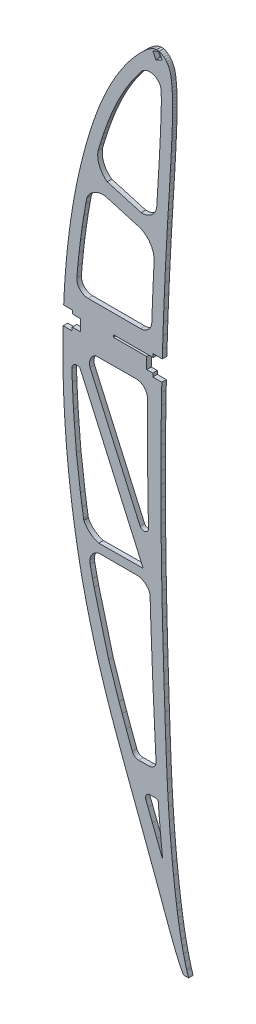
SolidWorks part; units mm, degrees
ref_plane "前视基准面" through (0, 0, 0) normal (0, 0, 1) x (1, 0, 0)
ref_plane "上视基准面" through (0, 0, 0) normal (0, 1, 0) x (1, 0, 0)
ref_plane "右视基准面" through (0, 0, 0) normal (1, 0, 0) x (0, 0, -1)
sketch "Model" plane through (0, 0, 0) normal (0, 0, 1) x (1, 0, 0)
  line L0 (913.8384, 184.2905) -> (912.3155, 187.0491)
  line L1 (912.3155, 187.0491) -> (911.2172, 189.5713)
  line L2 (911.2172, 189.5713) -> (910.1429, 192.0532)
  line L3 (910.1429, 192.0532) -> (909.1681, 194.525)
  line L4 (909.1681, 194.525) -> (908.2131, 197.0037)
  line L5 (908.2131, 197.0037) -> (907.2748, 199.4892)
  line L6 (907.2748, 199.4892) -> (906.3493, 201.9792)
  line L7 (906.3493, 201.9792) -> (905.4326, 204.4726)
  line L8 (905.4326, 204.4726) -> (904.519, 206.9671)
  line L9 (904.519, 206.9671) -> (903.6062, 209.4636)
  line L10 (903.6062, 209.4636) -> (901.77, 214.4493)
  line L11 (901.77, 214.4493) -> (899.921, 219.4284)
  line L12 (899.921, 219.4284) -> (898.0633, 224.4031)
  line L13 (898.0633, 224.4031) -> (896.1967, 229.3734)
  line L14 (896.1967, 229.3734) -> (894.3261, 234.3435)
  line L15 (894.3261, 234.3435) -> (892.4535, 239.3136)
  line L16 (892.4535, 239.3136) -> (890.5819, 244.2857)
  line L17 (890.5819, 244.2857) -> (888.7243, 249.2343)
  line L18 (888.7243, 249.2343) -> (886.8804, 254.1876)
  line L19 (886.8804, 254.1876) -> (885.0604, 259.147)
  line L20 (885.0604, 259.147) -> (883.2718, 264.1187)
  line L21 (883.2718, 264.1187) -> (881.5267, 269.1043)
  line L22 (881.5267, 269.1043) -> (879.8328, 274.1092)
  line L23 (879.8328, 274.1092) -> (878.2, 279.1357)
  line L24 (878.2, 279.1357) -> (876.669, 284.0757)
  line L25 (876.669, 284.0757) -> (875.2083, 289.0357)
  line L26 (875.2083, 289.0357) -> (873.8177, 294.0158)
  line L27 (873.8177, 294.0158) -> (872.4994, 299.015)
  line L28 (872.4994, 299.015) -> (871.2533, 304.0334)
  line L29 (871.2533, 304.0334) -> (870.0806, 309.0691)
  line L30 (870.0806, 309.0691) -> (868.983, 314.124)
  line L31 (868.983, 314.124) -> (867.9765, 319.1108)
  line L32 (867.9765, 319.1108) -> (867.0426, 324.1099)
  line L33 (867.0426, 324.1099) -> (866.1792, 329.121)
  line L34 (866.1792, 329.121) -> (865.3824, 334.143)
  line L35 (865.3824, 334.143) -> (864.6511, 339.1759)
  line L36 (864.6511, 339.1759) -> (863.9826, 344.2185)
  line L37 (863.9826, 344.2185) -> (863.3756, 349.2699)
  line L38 (863.3756, 349.2699) -> (862.8318, 354.2969)
  line L39 (862.8318, 354.2969) -> (862.3469, 359.3286)
  line L40 (862.3469, 359.3286) -> (861.9218, 364.3648)
  line L41 (861.9218, 364.3648) -> (861.5576, 369.4047)
  line L42 (861.5576, 369.4047) -> (861.2534, 374.4483)
  line L43 (861.2534, 374.4483) -> (861.0119, 379.4975)
  line L44 (861.0119, 379.4975) -> (860.8323, 384.5495)
  line L45 (860.8323, 384.5495) -> (860.7144, 389.6112)
  line L46 (860.7144, 389.6112) -> (860.6627, 394.6717)
  line L47 (860.6627, 394.6717) -> (860.6749, 399.7331)
  line L48 (860.6749, 399.7331) -> (860.7676, 405.5689)
  line L49 (904.2453, 405.7391) -> (904.1791, 401.7577)
  line L50 (904.1791, 401.7577) -> (904.0837, 396.6977)
  line L51 (904.0837, 396.6977) -> (904.0034, 391.6364)
  line L52 (904.0034, 391.6364) -> (903.9412, 386.5729)
  line L53 (903.9412, 386.5729) -> (903.8937, 381.516)
  line L54 (903.8937, 381.516) -> (903.8633, 376.4599)
  line L55 (903.8633, 376.4599) -> (903.8468, 371.4043)
  line L56 (903.8468, 371.4043) -> (903.8462, 366.3495)
  line L57 (903.8462, 366.3495) -> (903.8587, 361.2952)
  line L58 (903.8587, 361.2952) -> (903.8853, 356.2386)
  line L59 (903.8853, 356.2386) -> (903.9239, 351.1814)
  line L60 (903.9239, 351.1814) -> (903.9755, 346.1269)
  line L61 (903.9755, 346.1269) -> (904.0389, 341.0748)
  line L62 (904.0389, 341.0748) -> (904.1143, 336.0233)
  line L63 (904.1143, 336.0233) -> (904.2007, 330.9723)
  line L64 (904.2007, 330.9723) -> (904.2991, 325.9218)
  line L65 (904.2991, 325.9218) -> (904.4086, 320.8697)
  line L66 (904.4086, 320.8697) -> (904.5291, 315.8172)
  line L67 (904.5291, 315.8172) -> (904.6595, 310.7661)
  line L68 (904.6595, 310.7661) -> (904.8009, 305.7164)
  line L69 (904.8009, 305.7164) -> (904.9492, 300.6691)
  line L70 (904.9492, 300.6691) -> (905.1056, 295.6211)
  line L71 (905.1056, 295.6211) -> (905.2679, 290.5734)
  line L72 (905.2679, 290.5734) -> (905.4353, 285.5239)
  line L73 (905.4353, 285.5239) -> (905.6068, 280.4736)
  line L74 (905.6068, 280.4736) -> (905.7822, 275.4234)
  line L75 (905.7822, 275.4234) -> (905.9666, 270.3746)
  line L76 (905.9666, 270.3746) -> (906.1639, 265.3284)
  line L77 (906.1639, 265.3284) -> (906.3812, 260.2831)
  line L78 (906.3812, 260.2831) -> (906.6225, 255.2388)
  line L79 (906.6225, 255.2388) -> (906.8957, 250.195)
  line L80 (906.8957, 250.195) -> (907.205, 245.1526)
  line L81 (907.205, 245.1526) -> (907.5555, 240.1051)
  line L82 (907.5555, 240.1051) -> (907.9518, 235.0626)
  line L83 (907.9518, 235.0626) -> (908.395, 230.0242)
  line L84 (908.395, 230.0242) -> (908.8881, 224.9899)
  line L85 (908.8881, 224.9899) -> (909.4359, 219.961)
  line L86 (909.4359, 219.961) -> (910.0397, 214.9355)
  line L87 (910.0397, 214.9355) -> (910.7024, 209.9147)
  line L88 (910.7024, 209.9147) -> (911.0609, 207.3889)
  line L89 (911.0609, 207.3889) -> (911.4403, 204.866)
  line L90 (911.4403, 204.866) -> (911.8445, 202.3483)
  line L91 (911.8445, 202.3483) -> (912.2804, 199.8379)
  line L92 (912.2804, 199.8379) -> (912.7521, 197.3341)
  line L93 (912.7521, 197.3341) -> (913.2653, 194.8401)
  line L94 (913.2653, 194.8401) -> (913.8243, 192.3551)
  line L95 (913.8243, 192.3551) -> (914.4448, 189.8348)
  line L96 (914.4448, 189.8348) -> (915.1109, 187.3255)
  line L97 (915.1109, 187.3255) -> (915.2832, 186.7532)
  line L98 (915.2832, 186.7532) -> (916.0384, 184.2905)
  line L99 (882.9494, 412.239) -> (882.9494, 413.239)
  line L100 (882.9494, 413.239) -> (900.4381, 413.239)
  line L101 (903.1073, 531.427) -> (900.3814, 530.1739)
  line L102 (900.3814, 530.1739) -> (901.6334, 527.4489)
  line L103 (901.6334, 527.4489) -> (904.3594, 528.701)
  line L104 (904.3594, 528.701) -> (903.1073, 531.427)
  line L105 (882.9494, 412.239) -> (897.6033, 412.239)
  line L106 (869.4735, 449.5555) -> (869.8575, 452.0169)
  line L107 (869.8575, 452.0169) -> (870.7414, 457.0572)
  line L108 (870.7414, 457.0572) -> (871.2274, 459.6062)
  line L109 (876.1273, 479.9715) -> (876.8839, 482.5223)
  line L110 (876.8839, 482.5223) -> (877.6738, 485.0581)
  line L111 (877.6738, 485.0581) -> (878.4997, 487.5767)
  line L112 (878.4997, 487.5767) -> (879.365, 490.0807)
  line L113 (879.365, 490.0807) -> (880.273, 492.5783)
  line L114 (880.273, 492.5783) -> (880.7549, 493.8511)
  line L115 (880.7549, 493.8511) -> (881.251, 495.1262)
  line L116 (881.251, 495.1262) -> (881.7583, 496.3907)
  line L117 (881.7583, 496.3907) -> (882.2786, 497.6475)
  line L118 (882.2786, 497.6475) -> (882.8123, 498.8974)
  line L119 (882.8123, 498.8974) -> (883.3579, 500.1358)
  line L120 (883.3579, 500.1358) -> (883.9169, 501.3614)
  line L121 (883.9169, 501.3614) -> (884.5204, 502.6386)
  line L122 (884.5204, 502.6386) -> (885.1408, 503.9045)
  line L123 (885.1408, 503.9045) -> (885.7787, 505.1609)
  line L124 (885.7787, 505.1609) -> (886.4355, 506.4076)
  line L125 (886.4355, 506.4076) -> (887.1119, 507.6471)
  line L126 (887.1119, 507.6471) -> (887.8072, 508.8774)
  line L127 (887.8072, 508.8774) -> (888.5236, 510.0993)
  line L128 (888.5236, 510.0993) -> (889.3233, 511.4151)
  line L129 (889.3233, 511.4151) -> (890.1441, 512.7152)
  line L130 (890.1441, 512.7152) -> (890.9834, 513.9946)
  line L131 (890.9834, 513.9946) -> (891.84, 515.247)
  line L132 (891.84, 515.247) -> (892.712, 516.4692)
  line L133 (892.712, 516.4692) -> (893.5962, 517.6556)
  line L134 (893.5962, 517.6556) -> (894.4959, 518.8083)
  line L135 (894.4959, 518.8083) -> (894.6454, 518.9923)
  line L136 (903.9715, 515.9403) -> (903.9975, 514.9313)
  line L137 (903.9975, 514.9313) -> (904.0137, 513.707)
  line L138 (904.0137, 513.707) -> (904.0158, 512.4744)
  line L139 (904.0158, 512.4744) -> (904.0052, 511.2385)
  line L140 (904.0052, 511.2385) -> (903.983, 509.9924)
  line L141 (903.983, 509.9924) -> (903.9527, 508.7401)
  line L142 (903.9527, 508.7401) -> (903.9144, 507.4816)
  line L143 (903.9144, 507.4816) -> (903.8709, 506.2139)
  line L144 (903.8709, 506.2139) -> (903.8242, 504.9389)
  line L145 (903.8242, 504.9389) -> (903.7755, 503.6601)
  line L146 (903.7755, 503.6601) -> (903.7249, 502.3826)
  line L147 (903.7249, 502.3826) -> (903.6722, 501.1048)
  line L148 (903.6722, 501.1048) -> (903.6176, 499.8269)
  line L149 (903.6176, 499.8269) -> (903.561, 498.5508)
  line L150 (903.561, 498.5508) -> (903.5013, 497.2708)
  line L151 (903.5013, 497.2708) -> (903.4409, 495.9972)
  line L152 (903.4409, 495.9972) -> (903.311, 493.4393)
  line L153 (903.311, 493.4393) -> (903.1719, 490.8805)
  line L154 (903.1719, 490.8805) -> (903.0267, 488.3194)
  line L155 (903.0267, 488.3194) -> (902.8753, 485.756)
  line L156 (902.8753, 485.756) -> (902.7205, 483.1856)
  line L157 (902.7205, 483.1856) -> (902.5638, 480.6174)
  line L158 (902.5638, 480.6174) -> (902.406, 478.0458)
  line L159 (902.406, 478.0458) -> (902.2499, 475.4687)
  line L160 (902.2499, 475.4687) -> (902.0949, 472.8935)
  line L161 (902.0949, 472.8935) -> (902.0028, 471.3652)
  line L162 (900.8224, 449.6864) -> (900.5768, 444.5302)
  line L163 (900.5768, 444.5302) -> (900.3472, 439.3722)
  line L164 (900.3472, 439.3722) -> (900.1327, 434.2139)
  line L165 (900.1327, 434.2139) -> (899.8292, 426.3183)
  line L166 (894.8329, 421.5104) -> (871.8067, 421.5104)
  line L167 (866.8255, 426.9432) -> (867.2416, 431.7331)
  line L168 (867.2416, 431.7331) -> (867.7661, 436.8274)
  line L169 (867.7661, 436.8274) -> (868.3743, 441.9069)
  line L170 (868.3743, 441.9069) -> (869.0702, 446.9705)
  line L171 (869.0702, 446.9705) -> (869.4735, 449.5555)
  line L172 (897.9183, 396.3811) -> (897.9024, 393.3658)
  line L173 (897.9024, 393.3658) -> (897.8924, 388.2083)
  line L174 (869.7615, 336.4945) -> (869.1231, 340.5859)
  line L175 (869.1231, 340.5859) -> (868.4003, 345.6376)
  line L176 (865.157, 379.1332) -> (865.0474, 381.0069)
  line L177 (865.0474, 381.0069) -> (864.8146, 386.0729)
  line L178 (864.8146, 386.0729) -> (864.6437, 391.1474)
  line L179 (875.1445, 401.3147) -> (892.8985, 401.4074)
  line L180 (880.2019, 470.228) -> (895.1891, 465.9129)
  line L181 (879.3627, 464.3047) -> (894.6921, 459.8753)
  line L182 (861.0134, 413.5675) -> (861.1482, 416.6981)
  line L183 (861.1482, 416.6981) -> (861.4416, 421.8318)
  line L184 (861.4416, 421.8318) -> (861.8135, 427.0219)
  line L185 (861.8135, 427.0219) -> (862.2638, 432.2055)
  line L186 (862.2638, 432.2055) -> (862.7966, 437.3807)
  line L187 (862.7966, 437.3807) -> (863.4149, 442.5446)
  line L188 (863.4149, 442.5446) -> (864.1229, 447.6964)
  line L189 (864.1229, 447.6964) -> (864.9246, 452.8342)
  line L190 (864.9246, 452.8342) -> (865.8229, 457.9573)
  line L191 (865.8229, 457.9573) -> (866.3206, 460.5675)
  line L192 (866.3206, 460.5675) -> (866.8445, 463.1718)
  line L193 (866.8445, 463.1718) -> (867.3956, 465.7703)
  line L194 (867.3956, 465.7703) -> (867.9731, 468.362)
  line L195 (867.9731, 468.362) -> (868.5789, 470.9479)
  line L196 (868.5789, 470.9479) -> (869.212, 473.5279)
  line L197 (869.212, 473.5279) -> (869.8744, 476.1013)
  line L198 (869.8744, 476.1013) -> (870.5831, 478.7357)
  line L199 (870.5831, 478.7357) -> (871.3243, 481.3615)
  line L200 (871.3243, 481.3615) -> (872.1, 483.9768)
  line L201 (872.1, 483.9768) -> (872.9112, 486.5807)
  line L202 (872.9112, 486.5807) -> (873.7609, 489.1722)
  line L203 (873.7609, 489.1722) -> (874.6523, 491.7516)
  line L204 (874.6523, 491.7516) -> (875.5852, 494.3177)
  line L205 (875.5852, 494.3177) -> (876.0869, 495.6429)
  line L206 (876.0869, 495.6429) -> (876.6008, 496.9635)
  line L207 (876.6008, 496.9635) -> (877.128, 498.2778)
  line L208 (877.128, 498.2778) -> (877.6694, 499.5856)
  line L209 (877.6694, 499.5856) -> (878.2252, 500.8871)
  line L210 (878.2252, 500.8871) -> (878.7953, 502.1812)
  line L211 (878.7953, 502.1812) -> (879.3817, 503.467)
  line L212 (879.3817, 503.467) -> (880.0149, 504.8069)
  line L213 (880.0149, 504.8069) -> (880.6665, 506.1366)
  line L214 (880.6665, 506.1366) -> (881.3375, 507.4581)
  line L215 (881.3375, 507.4581) -> (882.0289, 508.7705)
  line L216 (882.0289, 508.7705) -> (882.7407, 510.0748)
  line L217 (882.7407, 510.0748) -> (883.4738, 511.372)
  line L218 (883.4738, 511.372) -> (884.2303, 512.6623)
  line L219 (884.2303, 512.6623) -> (885.0726, 514.0483)
  line L220 (885.0726, 514.0483) -> (885.9395, 515.4214)
  line L221 (885.9395, 515.4214) -> (886.8292, 516.7775)
  line L222 (886.8292, 516.7775) -> (887.741, 518.1106)
  line L223 (887.741, 518.1106) -> (888.6719, 519.4154)
  line L224 (888.6719, 519.4154) -> (889.6203, 520.688)
  line L225 (889.6203, 520.688) -> (890.5844, 521.9232)
  line L226 (890.5844, 521.9232) -> (891.1847, 522.6621)
  line L227 (891.1847, 522.6621) -> (891.7955, 523.3905)
  line L228 (891.7955, 523.3905) -> (892.4225, 524.1145)
  line L229 (892.4225, 524.1145) -> (893.0696, 524.8374)
  line L230 (893.0696, 524.8374) -> (893.7434, 525.5675)
  line L231 (893.7434, 525.5675) -> (894.4478, 526.3079)
  line L232 (894.4478, 526.3079) -> (895.1895, 527.065)
  line L233 (895.1895, 527.065) -> (896.223, 528.0831)
  line L234 (896.223, 528.0831) -> (897.3138, 529.0756)
  line L235 (897.3138, 529.0756) -> (898.4474, 529.9809)
  line L236 (898.4474, 529.9809) -> (899.6106, 530.7343)
  line L237 (899.6106, 530.7343) -> (900.7872, 531.2732)
  line L238 (900.7872, 531.2732) -> (901.964, 531.5338)
  line L239 (901.964, 531.5338) -> (903.1256, 531.4544)
  line L240 (903.1256, 531.4544) -> (903.8379, 531.2092)
  line L241 (903.8379, 531.2092) -> (904.5273, 530.8259)
  line L242 (904.5273, 530.8259) -> (905.1846, 530.3281)
  line L243 (905.1846, 530.3281) -> (905.8001, 529.7344)
  line L244 (905.8001, 529.7344) -> (906.3618, 529.0662)
  line L245 (906.3618, 529.0662) -> (906.8597, 528.3463)
  line L246 (906.8597, 528.3463) -> (907.2829, 527.593)
  line L247 (907.2829, 527.593) -> (907.5919, 526.9128)
  line L248 (907.5919, 526.9128) -> (907.8411, 526.2251)
  line L249 (907.8411, 526.2251) -> (908.0416, 525.5301)
  line L250 (908.0416, 525.5301) -> (908.2003, 524.8304)
  line L251 (908.2003, 524.8304) -> (908.3262, 524.1262)
  line L252 (908.3262, 524.1262) -> (908.4282, 523.417)
  line L253 (908.4282, 523.417) -> (908.5133, 522.706)
  line L254 (908.5133, 522.706) -> (908.6459, 521.4346)
  line L255 (908.6459, 521.4346) -> (908.7556, 520.1592)
  line L256 (908.7556, 520.1592) -> (908.8445, 518.8798)
  line L257 (908.8445, 518.8798) -> (908.9135, 517.5976)
  line L258 (908.9135, 517.5976) -> (908.9635, 516.3136)
  line L259 (908.9635, 516.3136) -> (908.9966, 515.0288)
  line L260 (908.9966, 515.0288) -> (909.0137, 513.7443)
  line L261 (909.0137, 513.7443) -> (909.0158, 512.4572)
  line L262 (909.0158, 512.4572) -> (909.0048, 511.1725)
  line L263 (909.0048, 511.1725) -> (908.9819, 509.8873)
  line L264 (908.9819, 509.8873) -> (908.9508, 508.6037)
  line L265 (908.9508, 508.6037) -> (908.9118, 507.3198)
  line L266 (908.9118, 507.3198) -> (908.8677, 506.0366)
  line L267 (908.8677, 506.0366) -> (908.8207, 504.7524)
  line L268 (908.8207, 504.7524) -> (908.7718, 503.466)
  line L269 (908.7718, 503.466) -> (908.7208, 502.1805)
  line L270 (908.7208, 502.1805) -> (908.6678, 500.895)
  line L271 (908.6678, 500.895) -> (908.6128, 499.6094)
  line L272 (908.6128, 499.6094) -> (908.5559, 498.3237)
  line L273 (908.5559, 498.3237) -> (908.4959, 497.0378)
  line L274 (908.4959, 497.0378) -> (908.4349, 495.752)
  line L275 (908.4349, 495.752) -> (908.3041, 493.1768)
  line L276 (908.3041, 493.1768) -> (908.1643, 490.6033)
  line L277 (908.1643, 490.6033) -> (908.0183, 488.0304)
  line L278 (908.0183, 488.0304) -> (907.8664, 485.4584)
  line L279 (907.8664, 485.4584) -> (907.7115, 482.8852)
  line L280 (907.7115, 482.8852) -> (907.5545, 480.3129)
  line L281 (907.5545, 480.3129) -> (907.3966, 477.7395)
  line L282 (907.3966, 477.7395) -> (907.2407, 475.1663)
  line L283 (907.2407, 475.1663) -> (907.0858, 472.5931)
  line L284 (907.0858, 472.5931) -> (906.9329, 470.02)
  line L285 (906.9329, 470.02) -> (906.783, 467.448)
  line L286 (906.783, 467.448) -> (906.635, 464.8751)
  line L287 (906.635, 464.8751) -> (906.4902, 462.3013)
  line L288 (906.4902, 462.3013) -> (906.3483, 459.7267)
  line L289 (906.3483, 459.7267) -> (906.0754, 454.5839)
  line L290 (906.0754, 454.5839) -> (905.8165, 449.4417)
  line L291 (905.8165, 449.4417) -> (905.5715, 444.3001)
  line L292 (905.5715, 444.3001) -> (905.3426, 439.1572)
  line L293 (905.3426, 439.1572) -> (905.1288, 434.014)
  line L294 (905.1288, 434.014) -> (904.931, 428.8695)
  line L295 (904.931, 428.8695) -> (904.7493, 423.7226)
  line L296 (904.7493, 423.7226) -> (904.5853, 418.5836)
  line L297 (904.5853, 418.5836) -> (904.4699, 414.7383)
  line L298 (902.6864, 244.8103) -> (902.7242, 244.2864)
  line L299 (902.7242, 244.2864) -> (902.7254, 244.2705)
  line L300 (902.7254, 244.2705) -> (903.1377, 239.115)
  line L301 (903.1377, 239.115) -> (903.5971, 233.953)
  line L302 (903.5971, 233.953) -> (904.1059, 228.7947)
  line L303 (904.1059, 228.7947) -> (904.6541, 223.7423)
  line L304 (904.6541, 223.7423) -> (903.9856, 225.4756)
  line L305 (903.9856, 225.4756) -> (902.0365, 230.5063)
  line L306 (902.0365, 230.5063) -> (900.0822, 235.5364)
  line L307 (900.0822, 235.5364) -> (898.1282, 240.563)
  line L308 (898.1282, 240.563) -> (897.1866, 242.9866)
  line L309 (899.0299, 245.7108) -> (901.6786, 245.7385)
  line L310 (869.7615, 336.4945) -> (869.8889, 335.8287)
  line L311 (880.8356, 288.1334) -> (885.4025, 274.4561)
  line L312 (876.4843, 330.4541) -> (896.0518, 330.6058)
  line L313 (866.6031, 360.017) -> (865.7013, 370.8882)
  line L314 (865.7013, 370.8882) -> (865.3433, 375.9453)
  line L315 (865.157, 379.1332) -> (865.3433, 375.9453)
  line L316 (874.4106, 312.5302) -> (873.7258, 315.5335)
  line L317 (873.7258, 315.5335) -> (872.6661, 320.5148)
  line L318 (872.6661, 320.5148) -> (872.5872, 322.0154)
  line L319 (899.0691, 322.3366) -> (899.245, 316.1982)
  line L320 (899.245, 316.1982) -> (899.432, 311.0605)
  line L321 (899.432, 311.0605) -> (900.1439, 292.4872)
  line L322 (901.0704, 272.5784) -> (901.1908, 270.0115)
  line L323 (901.1908, 270.0115) -> (901.7043, 259.63)
  line L324 (898.7394, 256.482) -> (894.084, 256.4332)
  line L325 (891.2403, 258.3885) -> (888.5766, 265.56)
  line L326 (888.5766, 265.56) -> (886.7672, 270.5596)
  line L327 (886.7672, 270.5596) -> (885.4025, 274.4561)
  line L328 (868.3583, 412.0689) -> (868.2684, 412.0689)
  line L329 (867.2684, 412.0689) -> (868.2684, 412.0689)
  line L330 (868.3583, 412.0689) -> (868.3583, 407.0689)
  line L331 (868.3583, 407.0689) -> (864.7756, 407.0689)
  line L332 (897.6033, 407.239) -> (900.2632, 407.239)
  line L333 (897.6033, 412.239) -> (897.6033, 407.239)
  line L334 (860.7676, 405.5689) -> (864.7756, 405.5689)
  line L335 (864.7756, 407.0689) -> (864.7756, 405.5689)
  line L336 (861.0134, 413.5675) -> (864.9488, 413.5675)
  line L337 (864.9488, 412.0689) -> (864.9488, 413.5675)
  line L338 (864.9488, 412.0689) -> (867.2684, 412.0689)
  line L339 (904.2453, 405.7391) -> (900.2632, 405.7391)
  line L340 (900.2632, 407.239) -> (900.2632, 405.7391)
  line L341 (904.4786, 414.7383) -> (900.4381, 414.7383)
  line L342 (900.4381, 413.239) -> (900.4381, 414.7383)
  line L343 (866.6031, 360.017) -> (868.4003, 345.6376)
  line L344 (874.4106, 312.5302) -> (880.8356, 288.1334)
  line L345 (900.1439, 292.4872) -> (901.0704, 272.5784)
  line L346 (897.9655, 372.0772) -> (897.8924, 388.2083)
  line L347 (894.6588, 346.0272) -> (872.6072, 395.5558)
  line L348 (896.0518, 330.6058) -> (868.2164, 393.1252)
  line L349 (893.1608, 326.6286) -> (876.4843, 326.6286)
  line L350 (916.0384, 184.2905) -> (913.8384, 184.2905)
  line L351 (898.3589, 347.0336) -> (897.9655, 372.0772)
  arc A0 (897.9183, 396.3811) -> (892.8985, 401.4074) centre (892.9183, 396.4074) ccw
  arc A1 (903.9715, 515.9403) -> (894.6454, 518.9923) centre (899.009, 516.5513) ccw
  arc A2 (876.1273, 479.9715) -> (880.2019, 470.228) centre (885.9573, 478.3585) ccw
  arc A3 (879.3627, 464.3047) -> (871.2274, 459.6062) centre (878.3525, 456.6614) ccw
  arc A4 (895.1891, 465.9129) -> (902.0028, 471.3652) centre (895.5719, 472.4183) ccw
  arc A5 (900.8224, 449.6864) -> (894.6921, 459.8753) centre (890.8059, 450.5985) ccw
  arc A6 (869.8889, 335.8287) -> (876.4843, 330.4541) centre (879.1785, 340.4944) ccw
  arc A7 (876.4843, 326.6286) -> (872.5872, 322.0154) centre (877.6699, 321.6745) ccw
  arc A8 (899.0691, 322.3366) -> (893.1133, 326.6286) centre (893.137, 320.3833) ccw
  arc A9 (894.6588, 346.0272) -> (898.3589, 347.0336) centre (896.3923, 346.9589) ccw
  arc A10 (875.1445, 401.3147) -> (872.6072, 395.5558) centre (877.1421, 396.9962) ccw
  arc A11 (868.2164, 393.1252) -> (864.6437, 391.1474) centre (866.865, 391.3505) ccw
  arc A12 (894.8329, 421.5104) -> (899.8292, 426.3183) centre (894.8329, 426.5104) ccw
  arc A13 (866.8255, 426.9432) -> (871.8067, 421.5104) centre (871.8067, 426.5104) ccw
  arc A14 (899.0299, 245.7108) -> (897.1866, 242.9866) centre (899.0508, 243.7109) ccw
  arc A15 (902.6864, 244.8103) -> (901.6786, 245.7385) centre (901.689, 244.7386) ccw
  arc A16 (898.7394, 256.482) -> (901.7043, 259.63) centre (898.708, 259.4818) ccw
  arc A17 (891.2403, 258.3885) -> (894.084, 256.4332) centre (894.0526, 259.4331) ccw
extrude "凸台-拉伸1" add sketch "Model" along normal blind 2 contours L350 L98 L97 L96 L95 L94 L93 L92 L91 L90 L89 L88 L87 L86 L85 L84 L83 L82 L81 L80 L79 L78 L77 L76 L75 L74 L73 L72 L71 L70 L69 L68 L67 L66 L65 L64 L63 L62 L61 L60 L59 L58 L57 L56 L55 L54 L53 L52 L51 L50 L49
